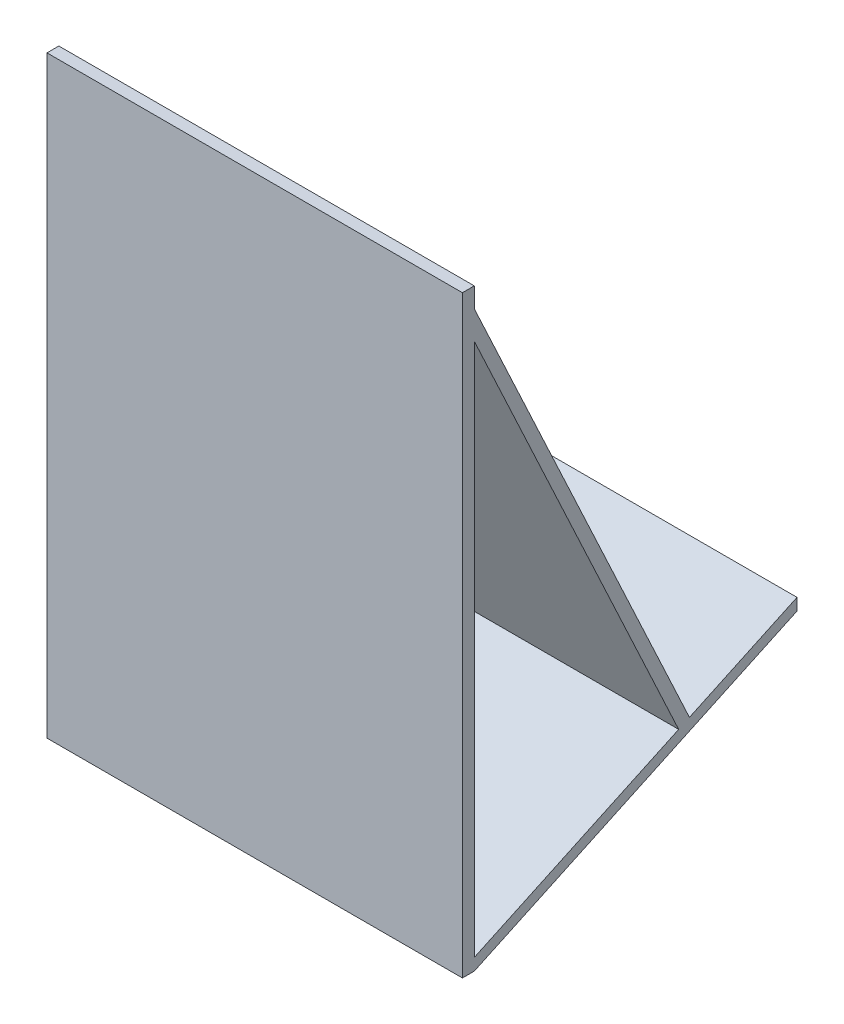
SolidWorks part; units mm, degrees
ref_plane "Plano frontal" through (0, 0, 0) normal (0, 0, 1) x (1, 0, 0)
ref_plane "Plano superior" through (0, 0, 0) normal (0, 1, 0) x (1, 0, 0)
ref_plane "Plano direito" through (0, 0, 0) normal (1, 0, 0) x (0, 0, -1)
sketch "Esboço2" plane through (0, 0, 0) normal (0, 0, 1) x (1, 0, 0)
  line L1 (-70, 100) -> (70, 100)
  line L2 (-70, 100) -> (-70, -100)
  line L3 (-70, -100) -> (70, -100)
  line L4 (70, 100) -> (70, -100)
  line L5 (-70, 100) -> (70, -100) construction
  line L6 (-70, -100) -> (70, 100) construction
  point P0 (0, 0)
  dimension "D1" = 140
  dimension "D2" = 200
extrude "Ressalto-extrusão2" add sketch "Esboço2" along normal blind 4
sketch3d "3DSketch2"
  line L0 (0, 0, 0) -> (0, -98, 0) construction
  line L2 (0, -98, 0) -> (0, -47.2858, -108.7569)
  line L10 (-70, -100, 0) -> (70, -100, 0) construction
  point P3 (0, -97.0613, 0)
  point P6 (0, -100, 0)
  point P7 (0, 0, 0)
  dimension "D1" = 65
  dimension "D2" = 2
  dimension "D4" = 120
ref_plane "Plano1" through (0, 0, -108.7569) normal (0, 0, 1) x (1, 0, 0)
sketch "Esboço11" plane through (0, 0, -108.7569) normal (0, 0, 1) x (1, 0, 0)
  line L1 (1, -45.2858) -> (-1, -45.2858)
  line L2 (1, -45.2858) -> (1, -49.2858)
  line L3 (1, -49.2858) -> (-1, -49.2858)
  line L4 (-1, -45.2858) -> (-1, -49.2858)
  line L5 (1, -45.2858) -> (-1, -49.2858) construction
  line L6 (1, -49.2858) -> (-1, -45.2858) construction
  point P0 (0, -47.2858)
  dimension "D1" = 2
  dimension "D2" = 4
sweep "Varredura1" add profiles "Esboço11" path "3DSketch2"
sketch "Esboço12" plane through (1, 0, 0) normal (1, 0, 0) x (0, 0, -1)
  line L4 (108.7569, -45.2858) -> (0, -96)
  line L5 (0, -96) -> (0, -100)
  line L6 (0, -100) -> (108.7569, -49.2858)
  line L7 (108.7569, -49.2858) -> (108.7569, -45.2858)
  line L8 (108.7569, -45.2858) -> (0, -96)
  line L9 (0, -96) -> (0, -100)
  line L10 (0, -100) -> (108.7569, -49.2858)
  line L11 (108.7569, -49.2858) -> (108.7569, -45.2858)
  dimension "D1" = 0
extrude "Ressalto-extrusão3" add sketch "Esboço12" along normal blind 69
sketch "Esboço13" plane through (-1, 0, 0) normal (-1, 0, 0) x (0, 0, 1)
  line L4 (-108.7569, -49.2858) -> (0, -100)
  line L5 (0, -100) -> (0, -96)
  line L6 (0, -96) -> (-108.7569, -45.2858)
  line L7 (-108.7569, -45.2858) -> (-108.7569, -49.2858)
  line L8 (-108.7569, -49.2858) -> (0, -100)
  line L9 (0, -100) -> (0, -96)
  line L10 (0, -96) -> (-108.7569, -45.2858)
  line L11 (-108.7569, -45.2858) -> (-108.7569, -49.2858)
  dimension "D1" = 0
extrude "Ressalto-extrusão4" add sketch "Esboço13" along normal blind 69
sketch "Esboço14" plane through (0, -78.8538, -36.7701) normal (0, 0.9063, 0.4226) x (1, 0, 0)
  line L0 (-70, -40.5714) -> (-70, 79.4286) construction
  line L1 (-70, 39.4286) -> (70, 39.4286)
  line L2 (-70, 39.4286) -> (-70, 35.4286)
  line L3 (-70, 35.4286) -> (70, 35.4286)
  line L4 (70, 39.4286) -> (70, 35.4286)
  line L5 (70, 79.4286) -> (70, -40.5714) construction
  line L6 (70, 79.4286) -> (-70, 79.4286) construction
  dimension "D1" = 40
  dimension "D2" = 4
extrude "Ressalto-extrusão5" add sketch "Esboço14" along normal blind 175
sketch "Esboço17" plane through (0, 0, 4) normal (0, 0, 1) x (1, 0, 0)
  line L0 (-70, 100) -> (-70, 95.2259) construction
  line L1 (-70, 96.2348) -> (70, 96.2348)
  line L2 (-70, 96.2348) -> (-70, 90.2348)
  line L3 (-70, 90.2348) -> (70, 90.2348)
  line L4 (70, 96.2348) -> (70, 90.2348)
  line L5 (70, -100) -> (70, 92.4093) construction
  dimension "D1" = 6
extrude "Ressalto-extrusão6" add sketch "Esboço17" along normal blind 10
sketch "Esboço18" plane through (0, 0, 14) normal (0, 0, 1) x (1, 0, 0)
  line L1 (-70, 96.2348) -> (70, 96.2348)
  line L2 (-70, 96.2348) -> (-70, 90.2348)
  line L3 (-70, 90.2348) -> (70, 90.2348)
  line L4 (70, 96.2348) -> (70, 90.2348)
extrude "Corte-extrusão1" cut sketch "Esboço18" against normal blind 10
